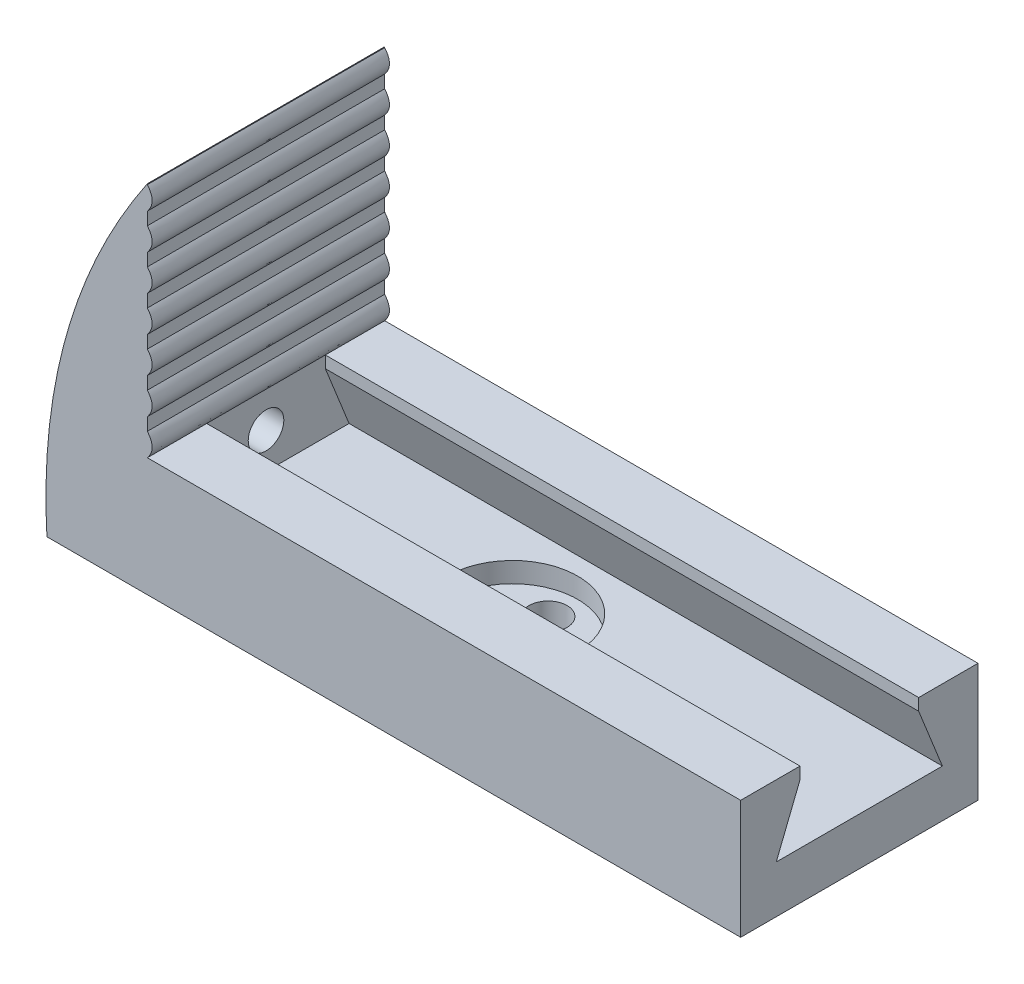
SolidWorks part; units mm, degrees
ref_plane "前视基准面" through (0, 0, 0) normal (0, 0, 1) x (1, 0, 0)
ref_plane "上视基准面" through (0, 0, 0) normal (0, 1, 0) x (1, 0, 0)
ref_plane "右视基准面" through (0, 0, 0) normal (1, 0, 0) x (0, 0, -1)
sketch "草图1" plane through (0, 0, 0) normal (0, 1, 0) x (1, 0, 0)
  line L1 (-25, -10) -> (25, -10)
  line L2 (-25, -10) -> (-25, 10)
  line L3 (-25, 10) -> (25, 10)
  line L4 (25, -10) -> (25, 10)
  line L5 (-25, -10) -> (25, 10) construction
  line L6 (-25, 10) -> (25, -10) construction
  point P0 (0, 0)
  dimension "D1" = 50
  dimension "D2" = 20
extrude "凸台-拉伸1" add sketch "草图1" along normal blind 10
sketch "草图2" plane through (-25, 0, 0) normal (-1, 0, 0) x (0, 0, 1)
  line L0 (0, 0) -> (0, 7.3512) construction
  line L1 (-6.3063, 4) -> (-3.4685, 4) construction
  line L2 (-10, 0) -> (10, 0) construction
  line L3 (7, 4) -> (-7, 4)
  line L4 (-5, 9) -> (5, 9)
  line L5 (-5, 9) -> (-7, 4)
  line L6 (5, 9) -> (7, 4)
  point P12 (0, 4)
  point P13 (0, 9)
  dimension "D1" = 4
  dimension "D2" = 7
  dimension "D3" = 5
  dimension "D4" = 5
extrude "切除-拉伸1" cut sketch "草图2" against normal blind 57
sketch "草图3" plane through (-25, 0, 0) normal (-1, 0, 0) x (0, 0, 1)
  line L0 (-5, 9) -> (-5, 16.6615)
  line L1 (-5, 16.6615) -> (-5, 24.5107)
  line L2 (5, 9) -> (5, 24.5107)
  line L3 (5, 24.5107) -> (-5, 24.5107)
  line L4 (-5, 9) -> (5, 9)
extrude "切除-拉伸2" cut sketch "草图3" against normal blind 57
sketch "草图5" plane through (0, 0, 10) normal (0, 0, 1) x (1, 0, 0)
  line L0 (-25, 0) -> (-25, 30)
  line L1 (-33.4631, 0) -> (-25, 0)
  spline S0 degree 2 poles (-25, 30) (-34.3943, 16.1499) (-33.4631, 0) knots 0 0 0 1 1 1
  dimension "D1" = 30
extrude "凸台-拉伸2" add sketch "草图5" against normal blind 20
sketch "草图6" plane through (0, 0, -10) normal (0, 0, -1) x (-1, 0, 0)
  line L0 (25, 10) -> (25, 30) construction
  line L1 (25, 11.9275) -> (25, 10)
  line L2 (25, 14.9275) -> (25, 13)
  line L3 (25, 17.9275) -> (25, 16)
  line L4 (25, 20.9275) -> (25, 19)
  line L5 (25, 23.9275) -> (25, 22)
  line L6 (25, 26.9275) -> (25, 25)
  line L7 (25, 29.9275) -> (25, 28)
  spline S0 degree 2 poles (25, 10) (24.1944, 10.9654) (25, 11.9275) knots 0 0 0 1 1 1
  spline S1 degree 2 poles (25, 13) (24.1944, 13.9654) (25, 14.9275) knots 0 0 0 1 1 1
  spline S2 degree 2 poles (25, 16) (24.1944, 16.9654) (25, 17.9275) knots 0 0 0 1 1 1
  spline S3 degree 2 poles (25, 19) (24.1944, 19.9654) (25, 20.9275) knots 0 0 0 1 1 1
  spline S4 degree 2 poles (25, 22) (24.1944, 22.9654) (25, 23.9275) knots 0 0 0 1 1 1
  spline S5 degree 2 poles (25, 25) (24.1944, 25.9654) (25, 26.9275) knots 0 0 0 1 1 1
  spline S6 degree 2 poles (25, 28) (24.1944, 28.9654) (25, 29.9275) knots 0 0 0 1 1 1
  dimension "D1" = 7
extrude "凸台-拉伸3" add sketch "草图6" against normal blind 20
sketch "草图7" plane through (-25, 0, 0) normal (1, 0, 0) x (0, 0, -1)
  line L0 (-10, 0) -> (10, 0) construction
  circle A0 centre (0, 7) radius 1.5
  dimension "D1" = 7
  dimension "D2" = 3
extrude "切除-拉伸3" cut sketch "草图7" against normal blind 16 and the other way blind 3
sketch "草图12" plane through (0, 0, 0) normal (0, -1, 0) x (1, 0, 0)
  line L0 (-4.2316, 10) -> (-4.2316, 2.8759) construction
  line L1 (-33.4631, 10) -> (25, 10) construction
  line L2 (25, 0) -> (16.1562, 0) construction
  line L3 (25, 10) -> (25, -10) construction
  circle A0 centre (-4.2316, 3) radius 1.6
  circle A1 centre (-4.2316, -3) radius 1.6
  circle A2 centre (-1.2316, 0) radius 1.6
  circle A3 centre (-7.2316, 0) radius 1.6
  dimension "D1" = 3
  dimension "D2" = 3
extrude "切除-拉伸4" cut sketch "草图12" against normal blind 13
sketch "草图13" plane through (0, 4, 0) normal (0, 1, 0) x (1, 0, 0)
  line L0 (-4.2316, 1.4) -> (-4.2316, 0.2801) construction
  circle A3 centre (-4.2316, 3) radius 1.6 construction
  circle A6 centre (-4.2316, 0) radius 5.5
extrude "切除-拉伸6" cut sketch "草图13" against normal blind 1.7
sketch "草图14" plane through (0, 0, -10) normal (0, 0, -1) x (-1, 0, 0)
  line L0 (0, 0) -> (0, 4.9986) construction
  line L2 (25, 30) -> (15.7231, 30)
  line L3 (-25, 10) -> (25, 10) construction
  dimension "D1" = 20
